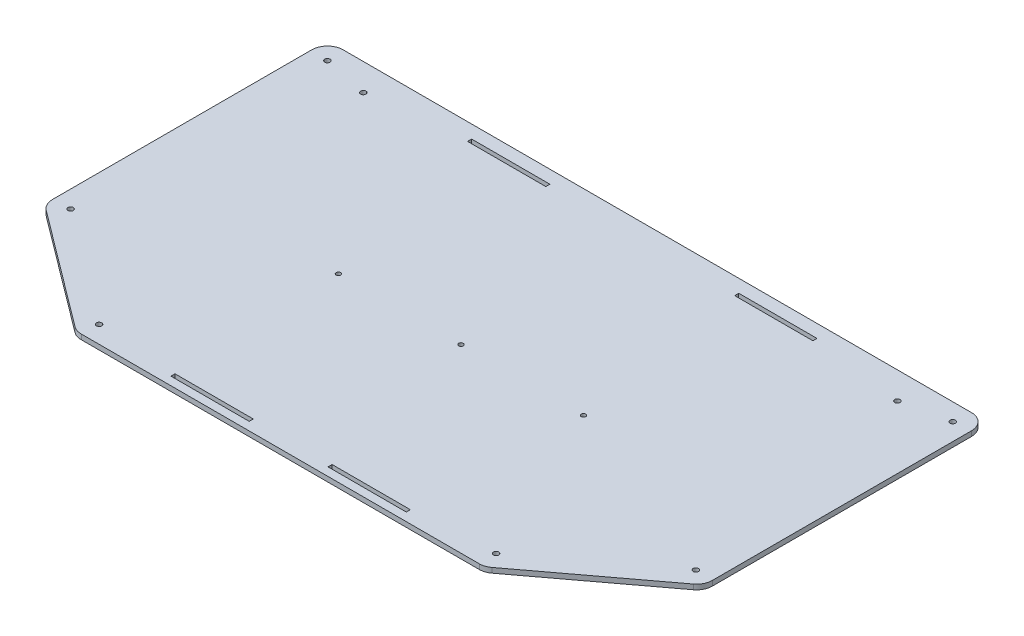
SolidWorks part; units mm, degrees
ref_plane "Front Plane" through (0, 0, 0) normal (0, 0, 1) x (1, 0, 0)
ref_plane "Top Plane" through (0, 0, 0) normal (0, 1, 0) x (1, 0, 0)
ref_plane "Right Plane" through (0, 0, 0) normal (1, 0, 0) x (0, 0, -1)
sketch "Sketch1" plane through (0, 0, 0) normal (0, 1, 0) x (1, 0, 0)
  line L0 (0, 240) -> (0, 60)
  line L1 (0, 0) -> (420, 0) construction
  line L2 (0, 0) -> (0, 240) construction
  line L3 (0, 240) -> (420, 240) construction
  line L4 (420, 0) -> (420, 240) construction
  line L5 (0, 60) -> (80, 0)
  line L6 (80, 0) -> (340, 0)
  line L7 (340, 0) -> (420, 60)
  line L8 (420, 60) -> (420, 240)
  line L9 (420, 240) -> (0, 240)
  line L10 (210, 0) -> (210, 240) construction
  dimension "D1" = 420
  dimension "D2" = 240
  dimension "D3" = 60
  dimension "D4" = 80
extrude "Boss-Extrude1" add sketch "Sketch1" along normal blind 3.175
fillet "Fillet1" radius 10 6 edges at (80, 1.5875, 0) (0, 1.5875, -60) (0, 1.5875, -240) (420, 1.5875, -240) (420, 1.5875, -60) (340, 1.5875, 0)
sketch "Sketch2" plane through (0, 3.175, 0) normal (0, 1, 0) x (1, 0, 0)
  line L0 (210, 240) -> (210, 0) construction
  line L1 (11, 65.5) -> (83.6667, 11) construction
  line L2 (1.0557, 60.5279) -> (120, 120) construction
  line L3 (80.1711, 0.5132) -> (120, 120) construction
  line L4 (2.9289, 237.0711) -> (11, 229) construction
  line L5 (11, 229) -> (40, 229) construction
  line L6 (132, 115) -> (288, 115) construction
  line L7 (132, 115) -> (0, 115) construction
  line L8 (288, 115) -> (420, 115) construction
  line L9 (40, 229) -> (40, 222.825) construction
  line L10 (83.3333, 0) -> (336.6667, 0) construction
  line L11 (410, 240) -> (10, 240) construction
  line L12 (0, 230) -> (0, 65) construction
  line L13 (4, 57) -> (77.3333, 2) construction
  line L14 (420, 65) -> (420, 230) construction
  circle A0 centre (11, 229) radius 1.7
  circle A1 centre (11, 65.5) radius 1.7
  circle A2 centre (83.6667, 11) radius 1.7
  circle A3 centre (409, 65.5) radius 1.7
  circle A4 centre (336.3333, 11) radius 1.7
  circle A5 centre (210, 115) radius 1.45
  circle A6 centre (132, 115) radius 1.45
  circle A7 centre (288, 115) radius 1.45
  circle A8 centre (40, 222.825) radius 1.7
  circle A9 centre (380, 222.825) radius 1.7
  circle A10 centre (409, 229) radius 1.7
  arc A11 (10, 240) -> (0, 230) centre (10, 230) ccw construction
  arc A12 (0, 65) -> (4, 57) centre (10, 65) ccw construction
  arc A13 (77.3333, 2) -> (83.3333, 0) centre (83.3333, 10) ccw construction
  point P12 (112.4409, 131.9434)
  point P21 (0, 0)
  point P28 (290.9172, 115)
  point P34 (120.2724, 142.8668)
  point P37 (210, 235)
  point P42 (2.9289, 232.0711)
  point P48 (1.0557, 60.5279)
  point P52 (80.1711, 0.5132)
  point P58 (9.3, 230.7)
  point P59 (0, 0)
  point P60 (49.5564, 145.8012)
  point P61 (0, 139.8903)
  point P62 (420, 137.4887)
  point P65 (146.3876, 115)
  point P66 (133.45, 115)
  point P67 (0, 0)
  dimension "D1" = 3.4
  dimension "D2" = 2.9
  dimension "D5" = 3.4
  dimension "D9" = 115
  dimension "D3" = 29
  dimension "D4" = 6.175
  dimension "D6" = 135
  dimension "D7" = 11
  dimension "D8" = 11
  dimension "D10" = 78
extrude "Cut-Extrude1" cut sketch "Sketch2" against normal up to surface (3.175 mm away) up to face at (210, 0, -99.1853)
sketch "Sketch6" plane through (0, 3.175, 0) normal (0, 1, 0) x (1, 0, 0)
  line L0 (0, 228.825) -> (420, 228.825) construction
  line L1 (0, 228.825) -> (0, 232)
  line L2 (0, 232) -> (420, 232) construction
  line L3 (420, 228.825) -> (420, 232) construction
  line L4 (100, 232) -> (150, 232) construction
  line L5 (100, 232) -> (100, 228.825) construction
  line L6 (100, 228.825) -> (150, 228.825) construction
  line L7 (150, 232) -> (150, 228.825) construction
  line L8 (73.3333, 5) -> (346.6667, 5) construction
  line L9 (73.3333, 5) -> (73.3333, 8.175)
  line L10 (73.3333, 8.175) -> (346.6667, 8.175) construction
  line L11 (346.6667, 5) -> (346.6667, 8.175) construction
  line L12 (100, 232) -> (150, 228.825) construction
  line L13 (210, 5) -> (210, 0) construction
  line L14 (135, 8.175) -> (185, 8.175) construction
  line L15 (135, 8.175) -> (135, 5) construction
  line L16 (135, 5) -> (185, 5) construction
  line L17 (185, 8.175) -> (185, 5) construction
  line L18 (150, 232) -> (100, 228.825) construction
  line L19 (135, 8.175) -> (185, 5) construction
  line L20 (100.1, 229.1125) -> (149.9, 229.1125)
  line L21 (100.1, 229.1125) -> (100.1, 231.7125)
  line L22 (100.1, 231.7125) -> (149.9, 231.7125)
  line L23 (149.9, 229.1125) -> (149.9, 231.7125)
  line L24 (100.1, 229.1125) -> (149.9, 231.7125) construction
  line L25 (100.1, 231.7125) -> (149.9, 229.1125) construction
  line L26 (135, 5) -> (185, 8.175) construction
  line L27 (284.9, 7.8875) -> (284.9, 5.2875)
  line L28 (135.1, 7.8875) -> (184.9, 7.8875)
  line L29 (135.1, 7.8875) -> (135.1, 5.2875)
  line L30 (135.1, 5.2875) -> (184.9, 5.2875)
  line L31 (184.9, 7.8875) -> (184.9, 5.2875)
  line L32 (135.1, 7.8875) -> (184.9, 5.2875) construction
  line L33 (135.1, 5.2875) -> (184.9, 7.8875) construction
  line L34 (284.9, 7.8875) -> (235.1, 7.8875)
  line L35 (235.1, 7.8875) -> (235.1, 5.2875)
  line L36 (284.9, 5.2875) -> (235.1, 5.2875)
  line L37 (210, 240) -> (210, 8.175) construction
  line L38 (270.1, 229.1125) -> (270.1, 231.7125)
  line L39 (319.9, 229.1125) -> (270.1, 229.1125)
  line L40 (319.9, 231.7125) -> (270.1, 231.7125)
  line L41 (319.9, 229.1125) -> (319.9, 231.7125)
  line L42 (83.3333, 0) -> (336.6667, 0) construction
  line L43 (4, 57) -> (77.3333, 2) construction
  line L44 (410, 240) -> (10, 240) construction
  line L45 (0, 230) -> (0, 65) construction
  line L46 (420, 65) -> (420, 230) construction
  point P15 (125, 230.4125)
  point P25 (160, 6.5875)
  point P46 (0, 228.825)
  point P47 (420, 229.1375)
  dimension "D1" = 3.175
  dimension "D2" = 50
  dimension "D3" = 50
  dimension "D4" = 49.8
  dimension "D5" = 2.6
  dimension "D6" = 25
  dimension "D7" = 2.6
  dimension "D8" = 49.8
  dimension "D9" = 5
  dimension "D10" = 8
  dimension "D11" = 100
extrude "Cut-Extrude2" cut sketch "Sketch6" against normal up to surface (3.175 mm away) contours L31 L28 L29 L30 | L22 L23 L20 L21 | L40 L38 L39 L41 | L34 L35 L36 L27 up to face at (210, 0, -113.55)
